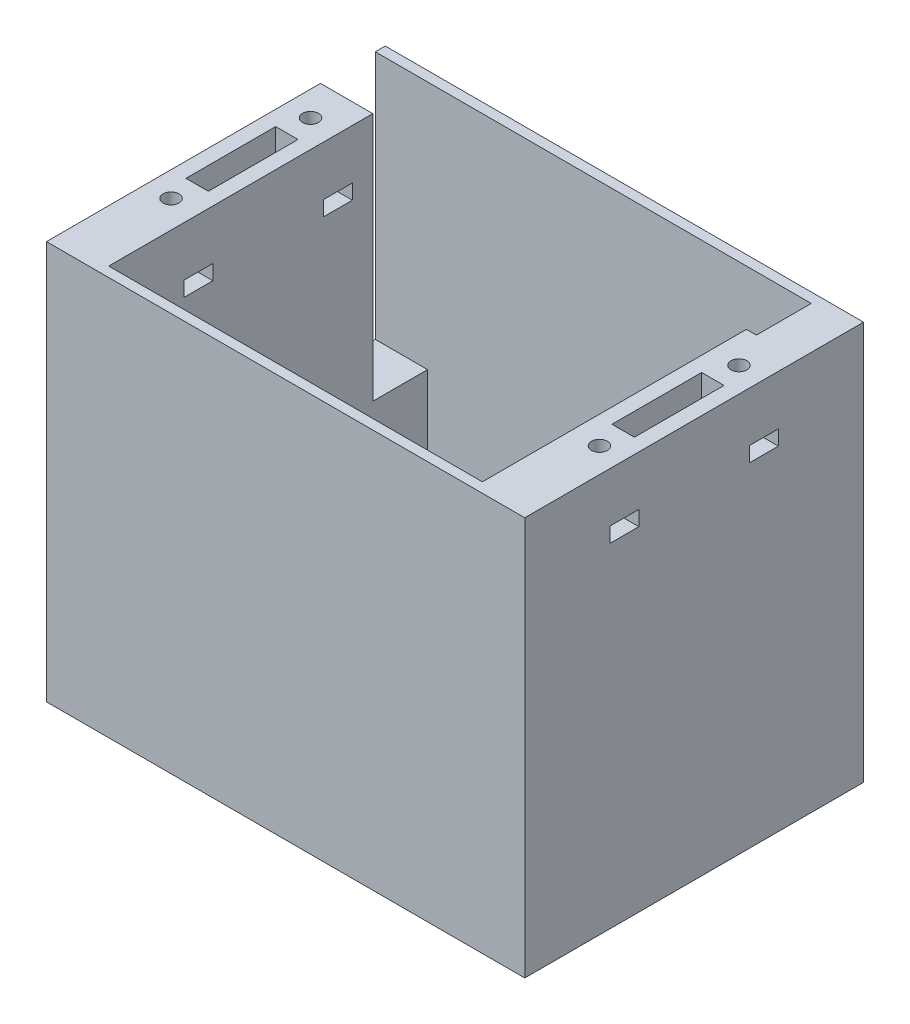
SolidWorks part; units mm, degrees
material "ABS"
ref_plane "Front Plane" through (0, 0, 0) normal (0, 0, 1) x (1, 0, 0)
ref_plane "Top Plane" through (0, 0, 0) normal (0, 1, 0) x (1, 0, 0)
ref_plane "Right Plane" through (0, 0, 0) normal (1, 0, 0) x (0, 0, -1)
sketch "Sketch1" plane through (0, 0, 0) normal (0, 1, 0) x (1, 0, 0)
  line L0 (0, -55) -> (0, 55) construction
  line L1 (-48, 34) -> (48, 34)
  line L2 (-48, 34) -> (-48, -34)
  line L3 (-48, -34) -> (48, -34)
  line L4 (48, 34) -> (48, -34)
  line L5 (-55, 0) -> (55, 0) construction
  dimension "D1" = 96
  dimension "D2" = 68
  dimension "D3" = 48
  dimension "D4" = 34
extrude "Boss-Extrude1" add sketch "Sketch1" along normal blind 80
sketch "Sketch2" plane through (0, 80, 0) normal (0, 1, 0) x (1, 0, 0)
  line L0 (-55, 0) -> (55, 0) construction
  line L1 (-37.5, 32) -> (37.5, 32)
  line L2 (-37.5, 32) -> (-37.5, -32)
  line L3 (-37.5, -32) -> (37.5, -32)
  line L4 (37.5, 32) -> (37.5, -32)
  line L6 (0, -55) -> (0, 55) construction
  line L7 (-17.5, 32) -> (-17.5, -39.2644) construction
  line L8 (-37.5, -2) -> (21.3338, -2) construction
  dimension "D1" = 64
  dimension "D2" = 32
  dimension "D3" = 75
  dimension "D4" = 37.5
  dimension "D5" = 20
  dimension "D6" = 30
extrude "Cut-Extrude1" cut sketch "Sketch2" against normal blind 45
sketch "Sketch3" plane through (0, 35, 0) normal (0, 1, 0) x (1, 0, 0)
  line L0 (59.9785, 12) -> (-60.8319, 12) construction
  line L1 (37.5, 32) -> (-37.5, 32) construction
  line L2 (26.5, 42.2907) -> (26.5, -52.7971) construction
  line L3 (-3.5, 44.2413) -> (-3.5, -47.9208) construction
  line L4 (37.5, -32) -> (37.5, 32) construction
  line L5 (68.3901, -20) -> (-57.9061, -20) construction
  line L6 (-37.5, -32) -> (37.5, -32) construction
  line L8 (-3.5, 12) -> (26.5, 12)
  line L9 (-3.5, 12) -> (-3.5, -20)
  line L10 (-3.5, -20) -> (26.5, -20)
  line L11 (26.5, 12) -> (26.5, -20)
  dimension "D1" = 20
  dimension "D2" = 11
  dimension "D3" = 30
  dimension "D4" = 12
extrude "Cut-Extrude2" cut sketch "Sketch3" against normal blind 8
sketch "Sketch9" plane through (0, 27, 0) normal (0, 1, 0) x (1, 0, 0)
  line L0 (11.5, 12) -> (11.5, -20) construction
  line L1 (26.5, 12) -> (-3.5, 12) construction
  line L2 (-3.5, -20) -> (26.5, -20) construction
  line L3 (-3.5, -4) -> (26.5, -4) construction
  line L4 (-3.5, 12) -> (-3.5, -20) construction
  line L5 (26.5, -20) -> (26.5, 12) construction
  circle A0 centre (11.5, -4) radius 1.8
  dimension "D1" = 3.6
extrude "Cut-Extrude5" cut sketch "Sketch9" against normal through all
chamfer "Chamfer1" distance 10 angle 45 1 edges at (11.5, 27, 5.8)
sketch "Sketch10" plane through (0, 0, 0) normal (0, -1, 0) x (1, 0, 0)
  circle A0 centre (11.5, 4) radius 3.8
  circle A1 centre (11.5, 4) radius 10
  dimension "D1" = 7.6
  dimension "D2" = 20
extrude "Cut-Extrude7" cut sketch "Sketch10" against normal blind 13
chamfer "Chamfer2" distance 3 angle 45 2 edges at (11.5, 13, -6) (11.5, 13, 0.2)
sketch "Sketch11" plane through (0, 35, 0) normal (0, 1, 0) x (1, 0, 0)
  line L0 (-37.5, 32) -> (37.5, 32)
  line L1 (-37.5, 32) -> (-37.5, -32) construction
  line L2 (37.5, -32) -> (37.5, 32) construction
  line L3 (37.5, 32) -> (37.5, -32)
  line L4 (37.5, -32) -> (-37.5, -32)
  line L5 (-37.5, -32) -> (-37.5, 32)
  line L6 (37.5, 32) -> (-37.5, 32) construction
  line L7 (-37.5, -32) -> (37.5, -32) construction
  line L8 (9.5, 32) -> (9.5, 16)
  line L10 (26.5, 12) -> (-3.5, 12) construction
  line L11 (-3.5, 12) -> (-3.5, -20) construction
  line L13 (-7.5, 2) -> (-37.5, 2)
  line L14 (-37.5, -2) -> (-7.5, -2)
  line L16 (13.5, -32) -> (13.5, -24)
  line L17 (13.5, -24) -> (30.5, -24)
  line L19 (9.5, -24) -> (9.5, -32)
  line L20 (11.5, -4) -> (11.5, 41.7025) construction
  line L21 (-44, 0) -> (44, 0) construction
  line L22 (9.5, 16) -> (-7.5, 16)
  line L23 (-7.5, 16) -> (-7.5, 2)
  line L24 (-7.5, -2) -> (-7.5, -24)
  line L25 (-7.5, -24) -> (9.5, -24)
  line L26 (30.5, -24) -> (30.5, -2)
  line L27 (30.5, -2) -> (37.5, -2)
  line L28 (37.5, -2) -> (37.5, -32)
  line L29 (13.5, -32) -> (37.5, -32)
  line L30 (26.5, -20) -> (26.5, 12) construction
  line L31 (-3.5, -20) -> (26.5, -20) construction
  line L32 (-3.5, -20) -> (26.5, -20) construction
  line L33 (37.5, 2) -> (30.5, 2)
  line L34 (30.5, 2) -> (30.5, 16)
  line L35 (30.5, 16) -> (13.5, 16)
  line L36 (13.5, 16) -> (13.5, 32)
  line L37 (13.5, 32) -> (37.5, 32)
  line M23 (-37.5, 32) -> (-37.5, -32)
  line M24 (-37.5, -32) -> (37.5, -32)
  line M25 (37.5, -32) -> (37.5, 32)
  line M26 (37.5, 32) -> (-37.5, 32)
  dimension "D1" = 0
  dimension "D2" = 0
  dimension "D3" = 2
  dimension "D4" = 2
  dimension "D5" = 2
  dimension "D6" = 2
  dimension "D7" = 4
  dimension "D8" = 4
  dimension "D9" = 4
  dimension "D10" = 4
  dimension "D11" = 4
  dimension "D12" = 2
  dimension "D13" = 2
  dimension "D14" = 2
  dimension "D15" = 4
  dimension "D16" = 2
extrude "Cut-Extrude8" cut sketch "Sketch11" against normal blind 25 contours L23 L22 L8 L0 L13 M23 | L25 L24 L14 L19 M23 M24 | L27 L26 L17 L16 L4 M25 | L36 L35 L34 L33 M25 M26
sketch "Sketch12" plane through (0, 80, 0) normal (0, 1, 0) x (1, 0, 0)
  line L0 (-48, 34) -> (-48, -34) construction
  line L1 (-45, 9) -> (-40.5, 9)
  line L2 (-45, 9) -> (-45, -9)
  line L3 (-45, -9) -> (-40.5, -9)
  line L4 (-40.5, 9) -> (-40.5, -9)
  line L5 (-37.5, 32) -> (-37.5, -32) construction
  line L6 (48, 34) -> (-48, 34) construction
  line L7 (-48, -34) -> (48, -34) construction
  line L8 (0, 40.6348) -> (0, -43.7381) construction
  line L9 (0, -37.4) -> (0, 37.4) construction
  line L10 (-57.3631, 0) -> (58.8638, 0) construction
  line L11 (45, -9) -> (40.5, -9)
  line L12 (40.5, 9) -> (40.5, -9)
  line L13 (45, 9) -> (45, -9)
  line L14 (45, 9) -> (40.5, 9)
  circle A0 centre (-43, 14) radius 1.6
  circle A1 centre (-43, -14) radius 1.6
  circle A2 centre (43, -14) radius 1.6
  circle A3 centre (43, 14) radius 1.6
  dimension "D7" = 3.2
  dimension "D1" = 3
  dimension "D2" = 3
  dimension "D3" = 25
  dimension "D4" = 25
  dimension "D5" = 20
  dimension "D6" = 5
extrude "Cut-Extrude9" cut sketch "Sketch12" against normal blind 70
sketch "Sketch13" plane through (-48, 0, 0) normal (-1, 0, 0) x (0, 0, 1)
  line L0 (0, 90.2473) -> (0, 6.1164) construction
  line L1 (-34, 80) -> (34, 80) construction
  line L2 (-16.9, 67) -> (-11.1, 67)
  line L3 (-16.9, 67) -> (-16.9, 70)
  line L4 (-16.9, 70) -> (-11.1, 70)
  line L5 (-34, 80) -> (-34, 0) construction
  line L6 (0, -44) -> (0, 44) construction
  line L7 (-11.1, 67) -> (-11.1, 70)
  line L8 (-16.9, 67) -> (-11.1, 70) construction
  line L9 (-16.9, 70) -> (-11.1, 67) construction
  line L10 (11.1, 67) -> (11.1, 70)
  line L11 (16.9, 67) -> (11.1, 67)
  line L12 (16.9, 67) -> (16.9, 70)
  line L13 (16.9, 70) -> (11.1, 70)
  point P0 (-14, 68.5)
  dimension "D1" = 20
  dimension "D2" = 3
  dimension "D3" = 5.8
  dimension "D4" = 10
extrude "Cut-Extrude10" cut sketch "Sketch13" against normal through all
sketch "Sketch15" plane through (0, 35, 0) normal (0, 1, 0) x (1, 0, 0)
  line L0 (-37.5, 32) -> (-37.5, 2) construction
  line L2 (-57.5, 28) -> (-57.5, 21)
  line L3 (-57.5, 21) -> (39.5, 21)
  line L4 (39.5, 28) -> (39.5, 21)
  line L5 (37.5, 2) -> (37.5, 32) construction
  line L7 (9.5, 32) -> (-37.5, 32) construction
  line L11 (-57.5, 28) -> (-57.5, 32)
  line L12 (-57.5, 32) -> (39.5, 32)
  line L13 (39.5, 28) -> (39.5, 32)
  dimension "D1" = 20
  dimension "D2" = 2
  dimension "D3" = 7
  dimension "D5" = 0
extrude "Cut-Extrude11" cut sketch "Sketch15" against normal blind 5 and the other way up to surface other way up to face at (43, 80, -15.6)
